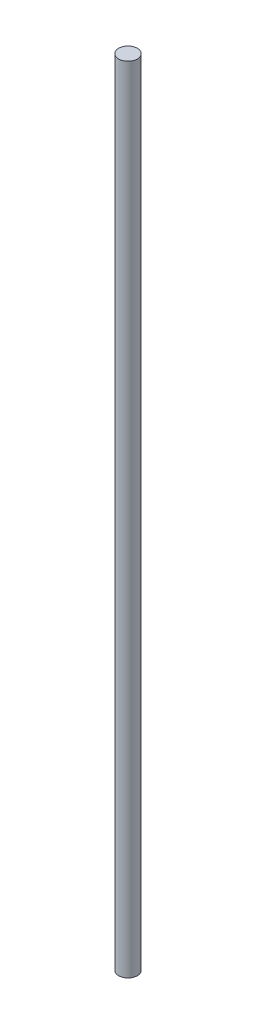
SolidWorks part; units mm, degrees
material "3004-H34，棒材(SS)"
ref_plane "前视基准面" through (0, 0, 0) normal (0, 0, 1) x (1, 0, 0)
ref_plane "上视基准面" through (0, 0, 0) normal (0, 1, 0) x (1, 0, 0)
ref_plane "右视基准面" through (0, 0, 0) normal (1, 0, 0) x (0, 0, -1)
sketch "草图1" plane through (0, 0, 0) normal (0, 1, 0) x (1, 0, 0)
  circle A0 centre (0, 0) radius 4
  dimension "D1" = 8
extrude "凸台-拉伸1" add sketch "草图1" along normal blind 340
